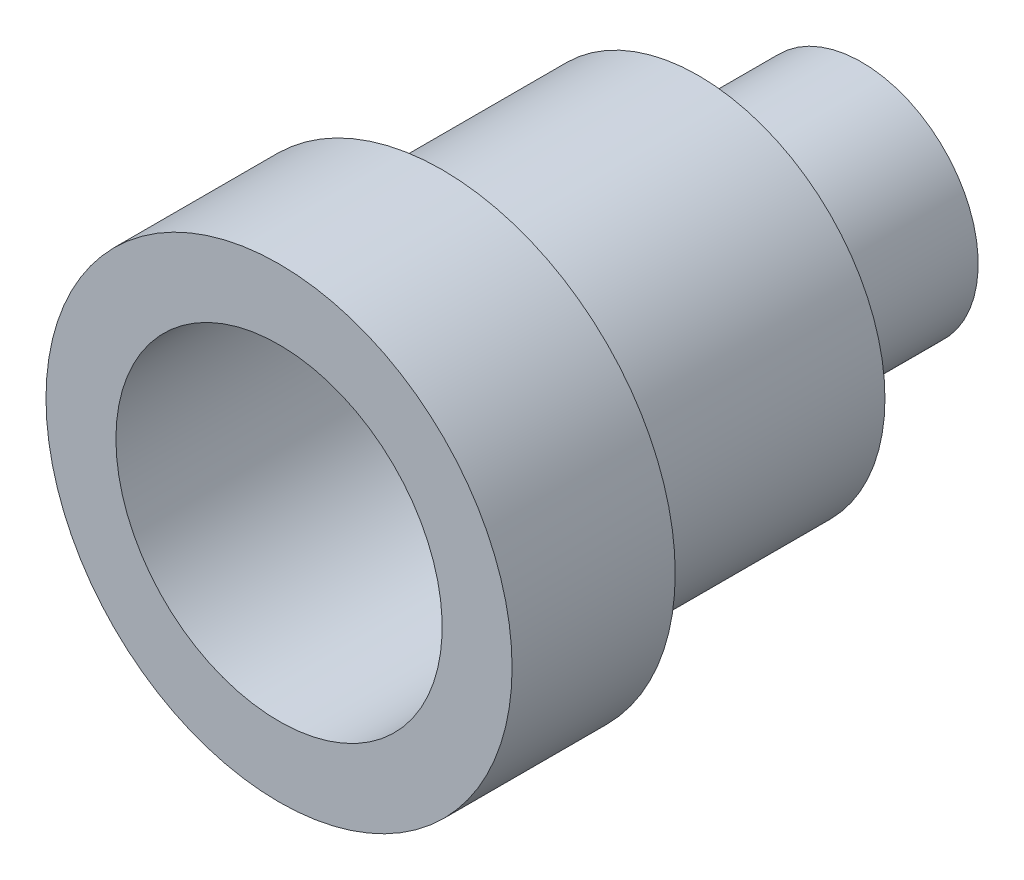
SolidWorks part; units mm, degrees
material "Polybutadiene (PB)"
ref_plane "Front Plane" through (0, 0, 0) normal (0, 0, 1) x (1, 0, 0)
ref_plane "Top Plane" through (0, 0, 0) normal (0, 1, 0) x (1, 0, 0)
ref_plane "Right Plane" through (0, 0, 0) normal (1, 0, 0) x (0, 0, -1)
sketch "Sketch1" plane through (0, 0, 0) normal (0, 1, 0) x (1, 0, 0)
  line L0 (-2818.542, 1223.1981) -> (-2821.042, 1223.1981)
  line L1 (-2823.542, 1223.1981) -> (-2823.542, 1216.1981)
  line L2 (-2821.042, 1223.1981) -> (-2821.042, 1214.2856)
  line L3 (-2815.542, 1216.1981) -> (-2818.542, 1216.1981)
  line L4 (-2823.542, 1216.1981) -> (-2823.542, 1205.1981)
  line L5 (-2813.542, 1205.1981) -> (-2814.542, 1205.1981)
  line L6 (-2823.542, 1205.1981) -> (-2823.542, 1198.1981)
  line L7 (-2816.542, 1211.2856) -> (-2816.542, 1198.1981)
  line L8 (-2818.542, 1223.1981) -> (-2818.542, 1216.1981)
  line L9 (-2815.542, 1216.1981) -> (-2815.542, 1206.1981)
  line L10 (-2813.542, 1205.1981) -> (-2813.542, 1198.1981)
  line L11 (-2813.542, 1198.1981) -> (-2816.542, 1198.1981)
  line L12 (-2816.542, 1211.2856) -> (-2818.542, 1211.2856)
  line L14 (-2820.1962, 1214.2856) -> (-2821.042, 1214.2856)
  line L15 (-2820.1962, 1214.2856) -> (-2820.1962, 1211.2856)
  line L16 (-2818.542, 1211.2856) -> (-2820.1962, 1211.2856)
  arc A0 (-2815.542, 1206.1981) -> (-2814.542, 1205.1981) centre (-2814.542, 1206.1981) ccw
  dimension "D1" = 2.5
  dimension "D3" = 7
revolve "Revolve1" add sketch "Sketch1" angle 360 about L4
sketch "Sketch2" plane through (0, 0, -1211.2856) normal (0, 0, 1) x (1, 0, 0)
  line L1 (-2819.3277, 0) -> (-2821.4349, 3.6497)
  line L2 (-2821.4349, 3.6497) -> (-2825.6491, 3.6497)
  line L3 (-2825.6491, 3.6497) -> (-2827.7563, 0)
  line L4 (-2827.7563, 0) -> (-2825.6491, -3.6497)
  line L5 (-2825.6491, -3.6497) -> (-2821.4349, -3.6497)
  line L6 (-2821.4349, -3.6497) -> (-2819.3277, 0)
  circle A0 centre (-2823.542, 0) radius 3.6497 construction
  dimension "D1" = 8.4286
extrude "Cut-Extrude2" cut sketch "Sketch2" against normal blind 2.5
